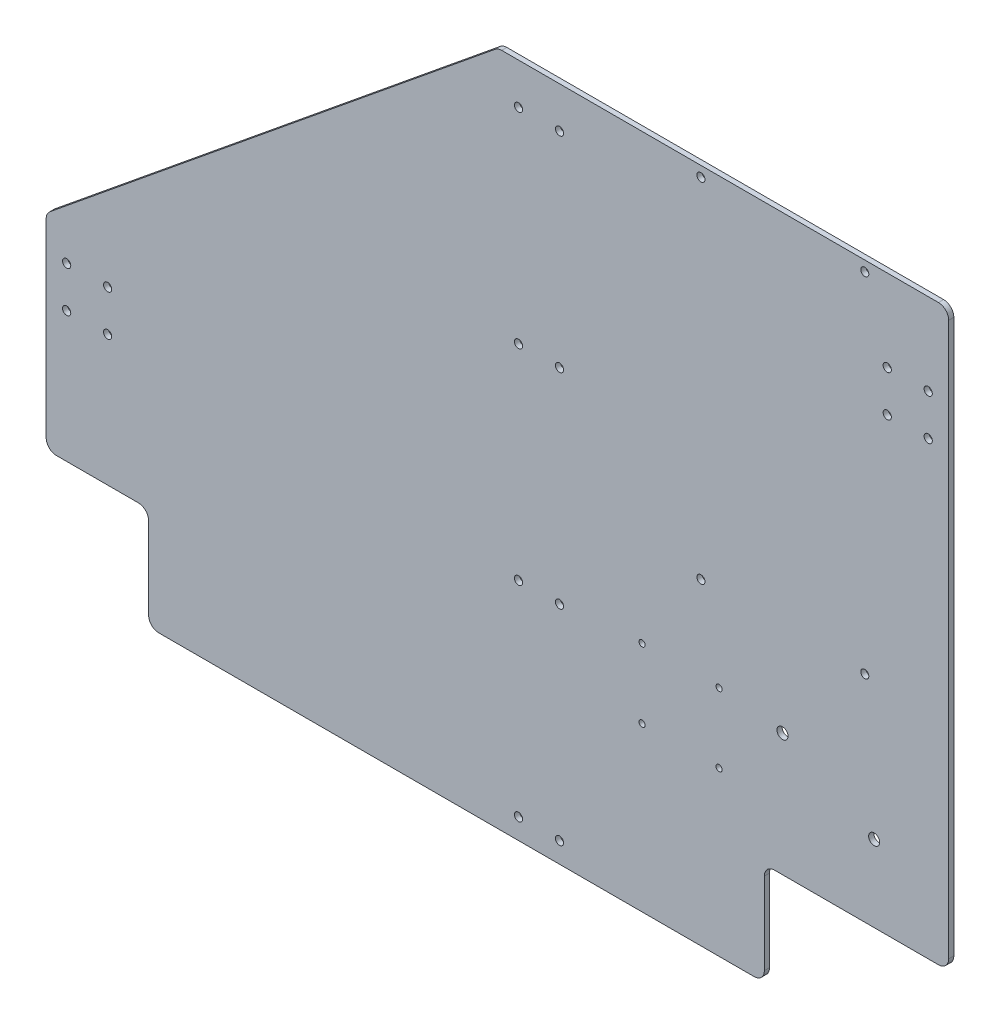
SolidWorks part; units mm, degrees
ref_plane "Front Plane" through (0, 0, 0) normal (0, 0, 1) x (1, 0, 0)
ref_plane "Top Plane" through (0, 0, 0) normal (0, 1, 0) x (1, 0, 0)
ref_plane "Right Plane" through (0, 0, 0) normal (1, 0, 0) x (0, 0, -1)
sketch "Sketch1" plane through (0, 0, 0) normal (0, 0, 1) x (1, 0, 0)
  line L1 (0, 0) -> (508.762, 0) construction
  line L2 (0, 0) -> (0, 419.1) construction
  line L3 (0, 419.1) -> (508.762, 419.1) construction
  line L4 (508.762, 0) -> (508.762, 419.1) construction
  line L5 (280.162, 0) -> (330.962, 0) construction
  line L6 (280.162, 0) -> (280.162, 419.1) construction
  line L7 (280.162, 419.1) -> (330.962, 419.1) construction
  line L8 (330.962, 0) -> (330.962, 419.1) construction
  line L9 (0, 0) -> (63.5, 0) construction
  line L10 (0, 0) -> (0, 63.5) construction
  line L11 (0, 63.5) -> (63.5, 63.5)
  line L12 (63.5, 0) -> (63.5, 63.5)
  line L13 (508.762, 0) -> (445.262, 0) construction
  line L14 (508.762, 0) -> (508.762, 63.5) construction
  line L15 (508.762, 63.5) -> (445.262, 63.5)
  line L16 (445.262, 0) -> (445.262, 63.5)
  line L17 (292.862, 12.7) -> (318.262, 12.7) construction
  line L18 (292.862, 12.7) -> (292.862, 139.7) construction
  line L19 (508.762, 63.5) -> (508.762, 419.1)
  line L20 (508.762, 419.1) -> (280.162, 419.1)
  line L21 (63.5, 0) -> (445.262, 0)
  line L22 (0, 63.5) -> (0, 190.5)
  line L23 (0, 190.5) -> (280.162, 419.1)
  line L24 (508.762, 419.1) -> (559.562, 419.1)
  line L25 (330.962, 381) -> (508.762, 381) construction
  line L26 (330.962, 381) -> (330.962, 330.2) construction
  line L27 (330.962, 330.2) -> (508.762, 330.2) construction
  line L28 (508.762, 381) -> (508.762, 330.2) construction
  line L29 (521.462, 368.3) -> (546.862, 368.3) construction
  line L30 (521.462, 368.3) -> (521.462, 342.9) construction
  line L31 (521.462, 342.9) -> (546.862, 342.9) construction
  line L32 (546.862, 368.3) -> (546.862, 342.9) construction
  line L33 (521.462, 368.3) -> (546.862, 342.9) construction
  line L34 (521.462, 342.9) -> (546.862, 368.3) construction
  line L35 (0, 0) -> (50.8, 0) construction
  line L36 (0, 0) -> (0, 182.5625) construction
  line L37 (0, 182.5625) -> (50.8, 182.5625) construction
  line L38 (50.8, 0) -> (50.8, 182.5625) construction
  line L39 (12.7, 169.8625) -> (38.1, 169.8625) construction
  line L40 (12.7, 169.8625) -> (12.7, 144.4625) construction
  line L41 (12.7, 144.4625) -> (38.1, 144.4625) construction
  line L42 (38.1, 169.8625) -> (38.1, 144.4625) construction
  line L43 (12.7, 169.8625) -> (38.1, 144.4625) construction
  line L44 (12.7, 144.4625) -> (38.1, 169.8625) construction
  line L45 (559.562, 419.1) -> (559.562, 63.5)
  line L46 (559.562, 63.5) -> (508.762, 63.5)
  circle A0 centre (318.262, 12.7) radius 2.54
  circle A1 centre (292.862, 12.7) radius 2.54
  circle A2 centre (292.862, 139.7) radius 2.54
  circle A3 centre (318.262, 139.7) radius 2.54
  circle A4 centre (292.862, 266.7) radius 2.54
  circle A5 centre (318.262, 266.7) radius 2.54
  circle A6 centre (292.862, 393.7) radius 2.54
  circle A7 centre (318.262, 393.7) radius 2.54
  circle A8 centre (521.462, 368.3) radius 2.54
  circle A9 centre (546.862, 368.3) radius 2.54
  circle A10 centre (546.862, 342.9) radius 2.54
  circle A11 centre (521.462, 342.9) radius 2.54
  circle A12 centre (12.7, 169.8625) radius 2.54
  circle A13 centre (38.1, 169.8625) radius 2.54
  circle A14 centre (38.1, 144.4625) radius 2.54
  circle A15 centre (12.7, 144.4625) radius 2.54
  point P41 (534.162, 355.6)
  point P53 (25.4, 157.1625)
  point P55 (25.4, 182.5625)
  dimension "D9" = 5.08
  dimension "D19" = 5.08
  dimension "D24" = 5.08
  dimension "20.03" = 508.762
  dimension "D2" = 419.1
  dimension "D3" = 50.8
  dimension "D4" = 177.8
  dimension "D5" = 63.5
  dimension "D6" = 63.5
  dimension "D7" = 25.4
  dimension "D8" = 12.7
  dimension "D10" = 12.7
  dimension "D12" = 127
  dimension "D13" = 127
  dimension "D14" = 50.8
  dimension "D15" = 38.1
  dimension "D16" = 12.7
  dimension "D17" = 12.7
  dimension "D18" = 25.4
  dimension "D20" = 182.5625
  dimension "D21" = 50.8
  dimension "D22" = 25.4
  dimension "D23" = 25.4
  dimension "D25" = 50.8
  dimension "D11" = 4
extrude "Boss-Extrude1" add sketch "Sketch1" along normal blind 3.175 contours L1 L16 L15 L4 L3 L2 L11 L12 | L46 L45 L24 L19
fillet "Fillet1" radius 6.35 9 edges at (280.162, 419.1, 1.5875) (445.262, 63.5, 1.5875) (445.262, 0, 1.5875) (63.5, 0, 1.5875) (63.5, 63.5, 1.5875) (0, 63.5, 1.5875) (0, 190.5, 1.5875) (559.562, 419.1, 1.5875) (559.562, 63.5, 1.5875)
sketch "Sketch2" plane through (0, 0, 3.175) normal (0, 0, 1) x (1, 0, 0)
  line L9 (167.64, 190.5) -> (167.64, 139.7) construction
  line L10 (116.84, 190.5) -> (116.84, 139.7) construction
  line L11 (66.04, 190.5) -> (66.04, 139.7) construction
  line L12 (0, 69.85) -> (0, 187.4857) construction
  line L13 (6.35, 63.5) -> (57.15, 63.5) construction
  circle A9 centre (66.04, 190.5) radius 2.54
  circle A10 centre (116.84, 190.5) radius 2.54
  circle A11 centre (167.64, 190.5) radius 2.54
  circle A12 centre (167.64, 139.7) radius 2.54
  circle A13 centre (116.84, 139.7) radius 2.54
  circle A14 centre (66.04, 139.7) radius 2.54
  dimension "D9" = 5.08
  dimension "D7" = 50.8
  dimension "D8" = 50.8
  dimension "D10" = 50.8
  dimension "D11" = 66.04
  dimension "D12" = 127
sketch "Sketch3" [suppressed] plane through (0, 0, 3.175) normal (0, 0, 1) x (1, 0, 0)
  line L1 (419.862, 228.6) -> (521.462, 228.6) construction
  line L2 (419.862, 228.6) -> (419.862, 101.6) construction
  line L3 (419.862, 101.6) -> (521.462, 101.6) construction
  line L4 (521.462, 228.6) -> (521.462, 101.6) construction
  line L5 (553.212, 63.5) -> (451.612, 63.5) construction
  line L7 (559.562, 412.75) -> (559.562, 69.85) construction
  circle A0 centre (521.462, 228.6) radius 1.4224
  circle A1 centre (419.862, 228.6) radius 1.4224
  circle A2 centre (419.862, 101.6) radius 1.4224
  circle A3 centre (521.462, 101.6) radius 1.4224
  dimension "D3" = 2.8448
  dimension "D1" = 101.6
  dimension "D2" = 127
  dimension "D4" = 38.1
  dimension "D5" = 38.1
extrude "Cut-Extrude3" [suppressed] cut sketch "Sketch3" against normal through all
sketch "Sketch4" [suppressed] plane through (0, 0, 3.175) normal (0, 0, 1) x (1, 0, 0)
  circle A0 centre (471.363, 392.8278) radius 19.113
extrude "Cut-Extrude4" [suppressed] cut sketch "Sketch4" against normal blind 1320.8
sketch "Sketch5" [suppressed] plane through (0, 0, 3.175) normal (0, 0, 1) x (1, 0, 0)
  line L1 (553.212, 419.1) -> (282.4239, 419.1) construction
  line L2 (559.562, 412.75) -> (559.562, 69.85) construction
  circle A0 centre (520.7, 398.145) radius 2.54
  circle A1 centre (497.84, 398.145) radius 2.54
  dimension "D2" = 5.08
  dimension "D1" = 38.862
  dimension "D3" = 22.86
  dimension "D4" = 20.955
extrude "Cut-Extrude5" [suppressed] cut sketch "Sketch5" against normal through all
sketch "Sketch6" plane through (0, 0, 0) normal (0, 0, -1) x (-1, 0, 0)
  circle A0 centre (-507.5341, 412.7222) radius 2.5
  circle A1 centre (-405.9341, 412.7222) radius 2.5
  circle A2 centre (-507.5341, 196.8222) radius 2.5
  circle A3 centre (-513.3621, 110.9575) radius 3.429
  circle A4 centre (-456.5246, 139.5278) radius 3.429
  arc A5 (-513.4, 114.3863) -> (-513.3242, 107.5287) centre (-513.3621, 110.9575) ccw construction
  arc A6 (-513.3242, 107.5287) -> (-513.4, 114.3863) centre (-513.3621, 110.9575) ccw construction
  circle A7 centre (-405.9341, 196.8222) radius 2.5
  circle A8 centre (-507.5341, 412.7222) radius 2.5 construction
  circle A9 centre (-417.195, 144.1893) radius 1.905
  circle A10 centre (-369.443, 144.1893) radius 1.905
  circle A11 centre (-417.1927, 101.1363) radius 1.905
  circle A12 centre (-369.443, 101.1363) radius 1.905
  circle A13 centre (-369.443, 101.1363) radius 1.905 construction
extrude "Cut-Extrude6" cut sketch "Sketch6" against normal blind 5.08
sketch "Sketch7" plane through (0, 0, 3.175) normal (0, 0, 1) x (1, 0, 0)
  line L0 (553.212, 419.1) -> (282.4239, 419.1) construction
  line L1 (280.162, 419.1) -> (330.962, 419.1)
  line L2 (280.162, 419.1) -> (280.162, 0)
  line L3 (280.162, 0) -> (330.962, 0)
  line L4 (330.962, 419.1) -> (330.962, 0)
  line L5 (69.85, 0) -> (438.912, 0) construction
  line L6 (559.562, 412.75) -> (559.562, 69.85) construction
  line L7 (330.962, 381) -> (559.562, 381)
  line L8 (330.962, 381) -> (330.962, 330.2)
  line L9 (330.962, 330.2) -> (559.562, 330.2)
  line L10 (559.562, 381) -> (559.562, 330.2)
  line L12 (280.162, 215.9) -> (242.062, 215.9)
  line L13 (280.162, 215.9) -> (280.162, 177.8)
  line L14 (280.162, 177.8) -> (242.062, 177.8)
  line L15 (242.062, 215.9) -> (242.062, 177.8)
  circle A0 centre (318.262, 393.7) radius 2.54 construction
  circle A1 centre (546.862, 368.3) radius 2.54 construction
  circle A2 centre (292.862, 266.7) radius 2.54 construction
  dimension "D2" = 12.7
  dimension "D4" = 12.7
  dimension "D1" = 50.8
  dimension "D3" = 50.8
  dimension "D5" = 50.8
  dimension "D6" = 38.1
  dimension "D7" = 38.1
